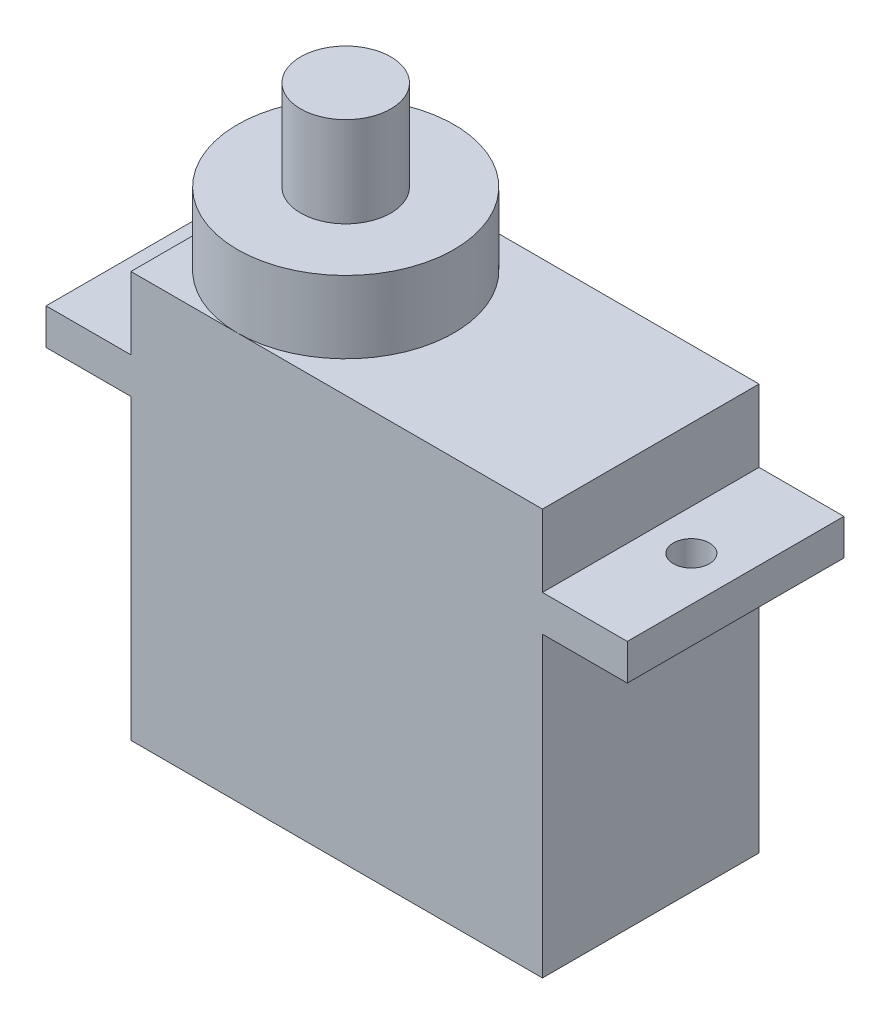
SolidWorks part; units mm, degrees
material "PVAL"
ref_plane "Front Plane" through (0, 0, 0) normal (0, 0, 1) x (1, 0, 0)
ref_plane "Top Plane" through (0, 0, 0) normal (0, 1, 0) x (1, 0, 0)
ref_plane "Right Plane" through (0, 0, 0) normal (1, 0, 0) x (0, 0, -1)
sketch "Sketch1" plane through (0, 0, 0) normal (0, 1, 0) x (1, 0, 0)
  line L1 (-11.4, -6) -> (11.4, -6)
  line L2 (-11.4, -6) -> (-11.4, 6)
  line L3 (-11.4, 6) -> (11.4, 6)
  line L4 (11.4, -6) -> (11.4, 6)
  line L5 (-11.4, -6) -> (11.4, 6) construction
  line L6 (-11.4, 6) -> (11.4, -6) construction
  point P0 (0, 0)
  dimension "D1" = 22.8
  dimension "D2" = 12
extrude "Boss-Extrude1" add sketch "Sketch1" along normal blind 22.5
sketch "Sketch2" plane through (11.4, 0, 0) normal (1, 0, 0) x (0, 0, -1)
  line L0 (-6, 22.5) -> (-6, 0) construction
  line L1 (-6, 18.5) -> (6, 18.5)
  line L2 (-6, 18.5) -> (-6, 16.5)
  line L3 (-6, 16.5) -> (6, 16.5)
  line L4 (6, 18.5) -> (6, 16.5)
  line L5 (6, 22.5) -> (6, 0) construction
  line L6 (-6, 22.5) -> (6, 22.5) construction
  dimension "D1" = 2
  dimension "D2" = 4
extrude "Boss-Extrude2" add sketch "Sketch2" along normal blind 4.7
mirror "Mirror1" about plane through (0, 0, 0) normal (1, 0, 0) of "Boss-Extrude2"
sketch "Sketch3" plane through (0, 22.5, 0) normal (0, 1, 0) x (1, 0, 0)
  circle A0 centre (-5.5, 0) radius 6
extrude "Boss-Extrude3" add sketch "Sketch3" along normal blind 4
sketch "Sketch4" plane through (0, 26.5, 0) normal (0, 1, 0) x (1, 0, 0)
  line L0 (-55, 0) -> (55, 0) construction
  circle A0 centre (-5.5, 0) radius 2.5
  arc A1 (-5.5, -6) -> (-5.5, 6) centre (-5.5, 0) ccw construction
extrude "Boss-Extrude4" add sketch "Sketch4" along normal blind 5
sketch "Sketch5" plane through (0, 18.5, 0) normal (0, 1, 0) x (1, 0, 0)
  line L0 (-55, 0) -> (55, 0) construction
  line L2 (16.1, 6) -> (16.1, -6) construction
  circle A0 centre (13.65, 0) radius 1
  dimension "D1" = 2.45
extrude "Cut-Extrude1" cut sketch "Sketch5" against normal blind 5
mirror "Mirror2" about plane through (0, 0, 0) normal (1, 0, 0) of "Cut-Extrude1"
